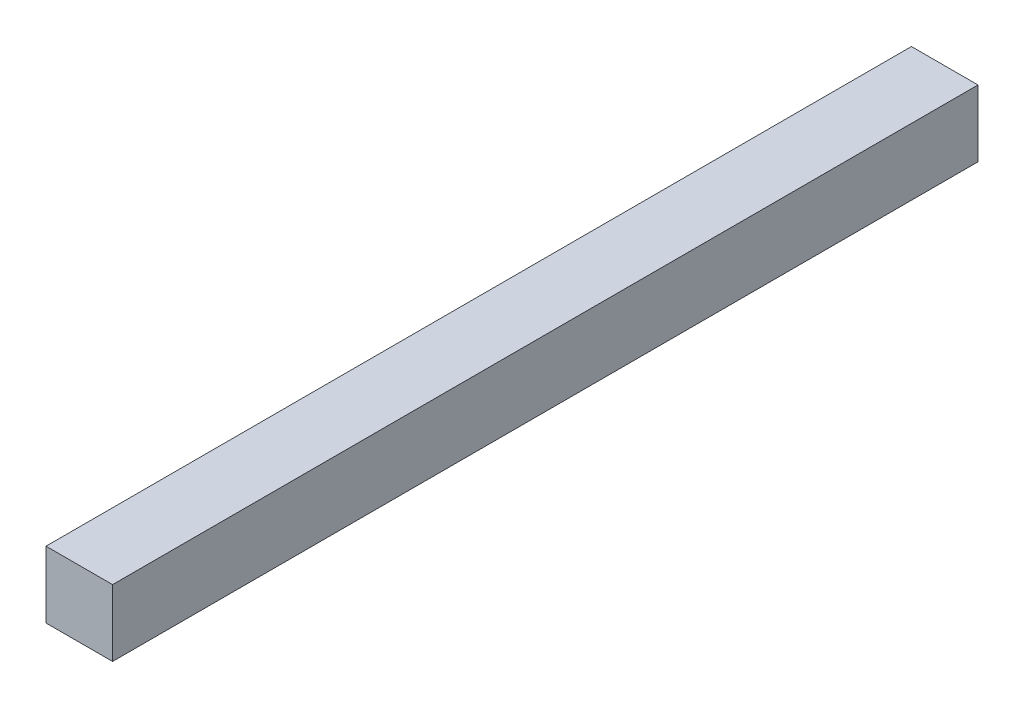
SolidWorks part; units mm, degrees
material "Brass"
ref_plane "Front Plane" through (0, 0, 0) normal (0, 0, 1) x (1, 0, 0)
ref_plane "Top Plane" through (0, 0, 0) normal (0, 1, 0) x (1, 0, 0)
ref_plane "Right Plane" through (0, 0, 0) normal (1, 0, 0) x (0, 0, -1)
sketch "Sketch1" plane through (0, 0, 0) normal (0, 0, 1) x (1, 0, 0)
  line L1 (0, 0) -> (6.35, 0)
  line L2 (0, 0) -> (0, 6.35)
  line L3 (0, 6.35) -> (6.35, 6.35)
  line L4 (6.35, 0) -> (6.35, 6.35)
  dimension "D1" = 6.35
  dimension "D2" = 6.35
extrude "Boss-Extrude1" add sketch "Sketch1" along normal blind 82.55
